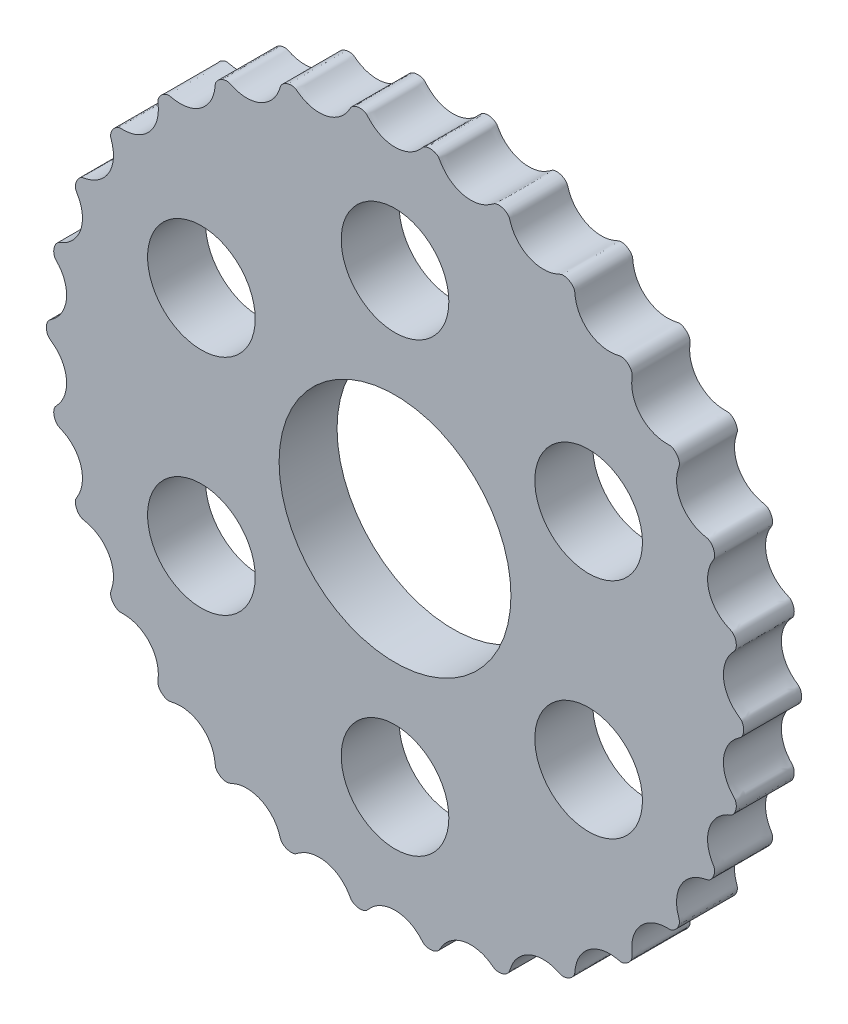
SolidWorks part; units mm, degrees
ref_plane "Front Plane" through (0, 0, 0) normal (0, 0, 1) x (1, 0, 0)
ref_plane "Top Plane" through (0, 0, 0) normal (0, 1, 0) x (1, 0, 0)
ref_plane "Right Plane" through (0, 0, 0) normal (1, 0, 0) x (0, 0, -1)
curve "Curve2"
sketch "Sketch4" plane through (0, 0, 0) normal (0, 0, 1) x (1, 0, 0)
  spline S0 degree 3 poles (2.0538, 40.2971) (0, 39.6094) (-2.0538, 40.2971) (-2.9937, 41.1501) (-3.2907, 41.4834) (-3.3948, 41.5967) (-3.4512, 41.6489) (-3.5086, 41.6916) (-3.588, 41.7387) (-3.6982, 41.7886) (-3.8407, 41.8344) (-4.0112, 41.8679) (-4.2015, 41.8823) (-4.4011, 41.8734) (-4.5981, 41.8406) (-4.7813, 41.787) (-4.9411, 41.7188) (-5.0709, 41.6443) (-5.1684, 41.5725) (-5.2363, 41.51) (-5.2836, 41.4563) (-5.3278, 41.3936) (-5.4061, 41.2611) (-5.6273, 40.8733) (-6.3694, 39.8436) (-8.2353, 38.7438) (-10.3871, 38.9896) (-11.4839, 39.6284) (-11.8437, 39.8927) (-11.9691, 39.9819) (-12.035, 40.0212) (-12.1001, 40.0511) (-12.1875, 40.0806) (-12.3058, 40.1065) (-12.4547, 40.1217) (-12.6284, 40.1191) (-12.8175, 40.0935) (-13.0109, 40.0433) (-13.1968, 39.9703) (-13.3648, 39.8798) (-13.5069, 39.7798) (-13.6184, 39.68) (-13.6989, 39.5895) (-13.7523, 39.5142) (-13.7873, 39.4518) (-13.8176, 39.3813) (-13.8666, 39.2354) (-14.0023, 38.8101) (-14.5141, 37.6486) (-16.1106, 36.1849) (-18.2665, 35.978) (-19.4721, 36.3748) (-19.879, 36.5586) (-20.0202, 36.6197) (-20.0929, 36.6444) (-20.1627, 36.6601) (-20.2544, 36.6708) (-20.3755, 36.6716) (-20.5243, 36.6555) (-20.6936, 36.6168) (-20.8734, 36.5525) (-21.052, 36.4632) (-21.2187, 36.3531) (-21.3642, 36.2296) (-21.4825, 36.1023) (-21.5708, 35.9815) (-21.6306, 35.8762) (-21.6672, 35.7915) (-21.6886, 35.7232) (-21.7035, 35.6479) (-21.7211, 35.495) (-21.7654, 35.0508) (-22.0246, 33.8083) (-23.2818, 32.0446) (-25.3476, 31.3939) (-26.6094, 31.5315) (-27.0456, 31.6265) (-27.1964, 31.657) (-27.2726, 31.6661) (-27.3442, 31.667) (-27.4361, 31.6583) (-27.5547, 31.6339) (-27.6969, 31.5872) (-27.8545, 31.5142) (-28.0169, 31.4139) (-28.1731, 31.2894) (-28.3132, 31.1471) (-28.4299, 30.996) (-28.5191, 30.8469) (-28.5804, 30.7104) (-28.6171, 30.595) (-28.6352, 30.5045) (-28.6419, 30.4332) (-28.6408, 30.3565) (-28.6263, 30.2033) (-28.5773, 29.7595) (-28.5724, 28.4903) (-29.4355, 26.5038) (-31.3209, 25.4378) (-32.5837, 25.31) (-33.0301, 25.3124) (-33.184, 25.3108) (-33.2604, 25.3038) (-33.3306, 25.2898) (-33.4187, 25.2622) (-33.5296, 25.2137) (-33.659, 25.1385) (-33.798, 25.0342) (-33.936, 24.9024) (-34.0629, 24.7482) (-34.1704, 24.5798) (-34.2531, 24.4078) (-34.3093, 24.2434) (-34.3409, 24.0971) (-34.3528, 23.9766) (-34.3517, 23.8843) (-34.3434, 23.8132) (-34.3264, 23.7384) (-34.2804, 23.5915) (-34.1402, 23.1677) (-33.8715, 21.9272) (-34.3027, 19.8047) (-35.9252, 18.3699) (-37.1339, 17.9824) (-37.571, 17.8919) (-37.7212, 17.8584) (-37.7945, 17.8356) (-37.8603, 17.8073) (-37.9407, 17.7621) (-38.0391, 17.6915) (-38.15, 17.591) (-38.2643, 17.4602) (-38.3719, 17.3025) (-38.464, 17.1253) (-38.5341, 16.9382) (-38.5793, 16.7528) (-38.6, 16.5803) (-38.6005, 16.4306) (-38.5871, 16.3103) (-38.5669, 16.2203) (-38.544, 16.1524) (-38.5118, 16.0828) (-38.4362, 15.9487) (-38.211, 15.5633) (-37.6902, 14.4057) (-37.6707, 12.24) (-38.9595, 10.4993) (-40.0612, 9.8689) (-40.47, 9.6894) (-40.6099, 9.6254) (-40.6769, 9.588) (-40.7353, 9.5466) (-40.8046, 9.4856) (-40.8861, 9.3961) (-40.9737, 9.2748) (-41.0583, 9.123) (-41.1308, 8.9465) (-41.184, 8.7539) (-41.2137, 8.5564) (-41.2193, 8.3656) (-41.2038, 8.1926) (-41.1731, 8.0461) (-41.135, 7.9312) (-41.0965, 7.8473) (-41.06, 7.7857) (-41.014, 7.7243) (-40.9122, 7.6089) (-40.6118, 7.2787) (-39.8617, 6.2547) (-39.3924, 4.1403) (-40.2911, 2.1697) (-41.2376, 1.324) (-41.6002, 1.0635) (-41.7237, 0.9718) (-41.7815, 0.9213) (-41.83, 0.8686) (-41.8851, 0.7946) (-41.9462, 0.6901) (-42.0067, 0.5532) (-42.0579, 0.3872) (-42.0921, 0.1994) (-42.1041, 0) (-42.0921, -0.1994) (-42.0579, -0.3872) (-42.0067, -0.5532) (-41.9462, -0.6901) (-41.8851, -0.7946) (-41.83, -0.8686) (-41.7815, -0.9213) (-41.7237, -0.9718) (-41.6002, -1.0635) (-41.2376, -1.324) (-40.2911, -2.1697) (-39.3924, -4.1403) (-39.8617, -6.2547) (-40.6118, -7.2787) (-40.9122, -7.6089) (-41.014, -7.7243) (-41.06, -7.7857) (-41.0965, -7.8473) (-41.135, -7.9312) (-41.1731, -8.0461) (-41.2038, -8.1926) (-41.2193, -8.3656) (-41.2137, -8.5564) (-41.184, -8.7539) (-41.1308, -8.9465) (-41.0583, -9.123) (-40.9737, -9.2748) (-40.8861, -9.3961) (-40.8046, -9.4856) (-40.7353, -9.5466) (-40.6769, -9.588) (-40.6099, -9.6254) (-40.47, -9.6894) (-40.0612, -9.8689) (-38.9595, -10.4993) (-37.6707, -12.24) (-37.6902, -14.4057) (-38.211, -15.5633) (-38.4362, -15.9487) (-38.5118, -16.0828) (-38.544, -16.1524) (-38.5669, -16.2203) (-38.5871, -16.3103) (-38.6005, -16.4306) (-38.6, -16.5803) (-38.5793, -16.7528) (-38.5341, -16.9382) (-38.464, -17.1253) (-38.3719, -17.3025) (-38.2643, -17.4602) (-38.15, -17.591) (-38.0391, -17.6915) (-37.9407, -17.7621) (-37.8603, -17.8073) (-37.7945, -17.8356) (-37.7212, -17.8584) (-37.571, -17.8919) (-37.1339, -17.9824) (-35.9252, -18.3699) (-34.3027, -19.8047) (-33.8715, -21.9272) (-34.1402, -23.1677) (-34.2804, -23.5915) (-34.3264, -23.7384) (-34.3434, -23.8132) (-34.3517, -23.8843) (-34.3528, -23.9766) (-34.3409, -24.0971) (-34.3093, -24.2434) (-34.2531, -24.4078) (-34.1704, -24.5798) (-34.0629, -24.7482) (-33.936, -24.9024) (-33.798, -25.0342) (-33.659, -25.1385) (-33.5296, -25.2137) (-33.4187, -25.2622) (-33.3306, -25.2898) (-33.2604, -25.3038) (-33.184, -25.3108) (-33.0301, -25.3124) (-32.5837, -25.31) (-31.3209, -25.4378) (-29.4355, -26.5038) (-28.5724, -28.4903) (-28.5773, -29.7595) (-28.6263, -30.2033) (-28.6408, -30.3565) (-28.6419, -30.4332) (-28.6352, -30.5045) (-28.6171, -30.595) (-28.5804, -30.7104) (-28.5191, -30.8469) (-28.4299, -30.996) (-28.3132, -31.1471) (-28.1731, -31.2894) (-28.0169, -31.4139) (-27.8545, -31.5142) (-27.6969, -31.5872) (-27.5547, -31.6339) (-27.4361, -31.6583) (-27.3442, -31.667) (-27.2726, -31.6661) (-27.1964, -31.657) (-27.0456, -31.6265) (-26.6094, -31.5315) (-25.3476, -31.3939) (-23.2818, -32.0446) (-22.0246, -33.8083) (-21.7654, -35.0508) (-21.7211, -35.495) (-21.7035, -35.6479) (-21.6886, -35.7232) (-21.6672, -35.7915) (-21.6306, -35.8762) (-21.5708, -35.9815) (-21.4825, -36.1023) (-21.3642, -36.2296) (-21.2187, -36.3531) (-21.052, -36.4632) (-20.8734, -36.5525) (-20.6936, -36.6168) (-20.5243, -36.6555) (-20.3755, -36.6716) (-20.2544, -36.6708) (-20.1627, -36.6601) (-20.0929, -36.6444) (-20.0202, -36.6197) (-19.879, -36.5586) (-19.4721, -36.3748) (-18.2665, -35.978) (-16.1106, -36.1849) (-14.5141, -37.6486) (-14.0023, -38.8101) (-13.8666, -39.2354) (-13.8176, -39.3813) (-13.7873, -39.4518) (-13.7523, -39.5142) (-13.6989, -39.5895) (-13.6184, -39.68) (-13.5069, -39.7798) (-13.3648, -39.8798) (-13.1968, -39.9703) (-13.0109, -40.0433) (-12.8175, -40.0935) (-12.6284, -40.1191) (-12.4547, -40.1217) (-12.3058, -40.1065) (-12.1875, -40.0806) (-12.1001, -40.0511) (-12.035, -40.0212) (-11.9691, -39.9819) (-11.8437, -39.8927) (-11.4839, -39.6284) (-10.3871, -38.9896) (-8.2353, -38.7438) (-6.3694, -39.8436) (-5.6273, -40.8733) (-5.4061, -41.2611) (-5.3278, -41.3936) (-5.2836, -41.4563) (-5.2363, -41.51) (-5.1684, -41.5725) (-5.0709, -41.6443) (-4.9411, -41.7188) (-4.7813, -41.787) (-4.5981, -41.8406) (-4.4011, -41.8734) (-4.2015, -41.8823) (-4.0112, -41.8679) (-3.8407, -41.8344) (-3.6982, -41.7886) (-3.588, -41.7387) (-3.5086, -41.6916) (-3.4512, -41.6489) (-3.3948, -41.5967) (-3.2907, -41.4834) (-2.9937, -41.1501) (-2.0538, -40.2971) (0, -39.6094) (2.0538, -40.2971) (2.9937, -41.1501) (3.2907, -41.4834) (3.3948, -41.5967) (3.4512, -41.6489) (3.5086, -41.6916) (3.588, -41.7387) (3.6982, -41.7886) (3.8407, -41.8344) (4.0112, -41.8679) (4.2015, -41.8823) (4.4011, -41.8734) (4.5981, -41.8406) (4.7813, -41.787) (4.9411, -41.7188) (5.0709, -41.6443) (5.1684, -41.5725) (5.2363, -41.51) (5.2836, -41.4563) (5.3278, -41.3936) (5.4061, -41.2611) (5.6273, -40.8733) (6.3694, -39.8436) (8.2353, -38.7438) (10.3871, -38.9896) (11.4839, -39.6284) (11.8437, -39.8927) (11.9691, -39.9819) (12.035, -40.0212) (12.1001, -40.0511) (12.1875, -40.0806) (12.3058, -40.1065) (12.4547, -40.1217) (12.6284, -40.1191) (12.8175, -40.0935) (13.0109, -40.0433) (13.1968, -39.9703) (13.3648, -39.8798) (13.5069, -39.7798) (13.6184, -39.68) (13.6989, -39.5895) (13.7523, -39.5142) (13.7873, -39.4518) (13.8176, -39.3813) (13.8666, -39.2354) (14.0023, -38.8101) (14.5141, -37.6486) (16.1106, -36.1849) (18.2665, -35.978) (19.4721, -36.3748) (19.879, -36.5586) (20.0202, -36.6197) (20.0929, -36.6444) (20.1627, -36.6601) (20.2544, -36.6708) (20.3755, -36.6716) (20.5243, -36.6555) (20.6936, -36.6168) (20.8734, -36.5525) (21.052, -36.4632) (21.2187, -36.3531) (21.3642, -36.2296) (21.4825, -36.1023) (21.5708, -35.9815) (21.6306, -35.8762) (21.6672, -35.7915) (21.6886, -35.7232) (21.7035, -35.6479) (21.7211, -35.495) (21.7654, -35.0508) (22.0246, -33.8083) (23.2818, -32.0446) (25.3476, -31.3939) (26.6094, -31.5315) (27.0456, -31.6265) (27.1964, -31.657) (27.2726, -31.6661) (27.3442, -31.667) (27.4361, -31.6583) (27.5547, -31.6339) (27.6969, -31.5872) (27.8545, -31.5142) (28.0169, -31.4139) (28.1731, -31.2894) (28.3132, -31.1471) (28.4299, -30.996) (28.5191, -30.8469) (28.5804, -30.7104) (28.6171, -30.595) (28.6352, -30.5045) (28.6419, -30.4332) (28.6408, -30.3565) (28.6263, -30.2033) (28.5773, -29.7595) (28.5724, -28.4903) (29.4355, -26.5038) (31.3209, -25.4378) (32.5837, -25.31) (33.0301, -25.3124) (33.184, -25.3108) (33.2604, -25.3038) (33.3306, -25.2898) (33.4187, -25.2622) (33.5296, -25.2137) (33.659, -25.1385) (33.798, -25.0342) (33.936, -24.9024) (34.0629, -24.7482) (34.1704, -24.5798) (34.2531, -24.4078) (34.3093, -24.2434) (34.3409, -24.0971) (34.3528, -23.9766) (34.3517, -23.8843) (34.3434, -23.8132) (34.3264, -23.7384) (34.2804, -23.5915) (34.1402, -23.1677) (33.8715, -21.9272) (34.3027, -19.8047) (35.9252, -18.3699) (37.1339, -17.9824) (37.571, -17.8919) (37.7212, -17.8584) (37.7945, -17.8356) (37.8603, -17.8073) (37.9407, -17.7621) (38.0391, -17.6915) (38.15, -17.591) (38.2643, -17.4602) (38.3719, -17.3025) (38.464, -17.1253) (38.5341, -16.9382) (38.5793, -16.7528) (38.6, -16.5803) (38.6005, -16.4306) (38.5871, -16.3103) (38.5669, -16.2203) (38.544, -16.1524) (38.5118, -16.0828) (38.4362, -15.9487) (38.211, -15.5633) (37.6902, -14.4057) (37.6707, -12.24) (38.9595, -10.4993) (40.0612, -9.8689) (40.47, -9.6894) (40.6099, -9.6254) (40.6769, -9.588) (40.7353, -9.5466) (40.8046, -9.4856) (40.8861, -9.3961) (40.9737, -9.2748) (41.0583, -9.123) (41.1308, -8.9465) (41.184, -8.7539) (41.2137, -8.5564) (41.2193, -8.3656) (41.2038, -8.1926) (41.1731, -8.0461) (41.135, -7.9312) (41.0965, -7.8473) (41.06, -7.7857) (41.014, -7.7243) (40.9122, -7.6089) (40.6118, -7.2787) (39.8617, -6.2547) (39.3924, -4.1403) (40.2911, -2.1697) (41.2376, -1.324) (41.6002, -1.0635) (41.7237, -0.9718) (41.7815, -0.9213) (41.83, -0.8686) (41.8851, -0.7946) (41.9462, -0.6901) (42.0067, -0.5532) (42.0579, -0.3872) (42.0921, -0.1994) (42.1041, 0) (42.0921, 0.1994) (42.0579, 0.3872) (42.0067, 0.5532) (41.9462, 0.6901) (41.8851, 0.7946) (41.83, 0.8686) (41.7815, 0.9213) (41.7237, 0.9718) (41.6002, 1.0635) (41.2376, 1.324) (40.2911, 2.1697) (39.3924, 4.1403) (39.8617, 6.2547) (40.6118, 7.2787) (40.9122, 7.6089) (41.014, 7.7243) (41.06, 7.7857) (41.0965, 7.8473) (41.135, 7.9312) (41.1731, 8.0461) (41.2038, 8.1926) (41.2193, 8.3656) (41.2137, 8.5564) (41.184, 8.7539) (41.1308, 8.9465) (41.0583, 9.123) (40.9737, 9.2748) (40.8861, 9.3961) (40.8046, 9.4856) (40.7353, 9.5466) (40.6769, 9.588) (40.6099, 9.6254) (40.47, 9.6894) (40.0612, 9.8689) (38.9595, 10.4993) (37.6707, 12.24) (37.6902, 14.4057) (38.211, 15.5633) (38.4362, 15.9487) (38.5118, 16.0828) (38.544, 16.1524) (38.5669, 16.2203) (38.5871, 16.3103) (38.6005, 16.4306) (38.6, 16.5803) (38.5793, 16.7528) (38.5341, 16.9382) (38.464, 17.1253) (38.3719, 17.3025) (38.2643, 17.4602) (38.15, 17.591) (38.0391, 17.6915) (37.9407, 17.7621) (37.8603, 17.8073) (37.7945, 17.8356) (37.7212, 17.8584) (37.571, 17.8919) (37.1339, 17.9824) (35.9252, 18.3699) (34.3027, 19.8047) (33.8715, 21.9272) (34.1402, 23.1677) (34.2804, 23.5915) (34.3264, 23.7384) (34.3434, 23.8132) (34.3517, 23.8843) (34.3528, 23.9766) (34.3409, 24.0971) (34.3093, 24.2434) (34.2531, 24.4078) (34.1704, 24.5798) (34.0629, 24.7482) (33.936, 24.9024) (33.798, 25.0342) (33.659, 25.1385) (33.5296, 25.2137) (33.4187, 25.2622) (33.3306, 25.2898) (33.2604, 25.3038) (33.184, 25.3108) (33.0301, 25.3124) (32.5837, 25.31) (31.3209, 25.4378) (29.4355, 26.5038) (28.5724, 28.4903) (28.5773, 29.7595) (28.6263, 30.2033) (28.6408, 30.3565) (28.6419, 30.4332) (28.6352, 30.5045) (28.6171, 30.595) (28.5804, 30.7104) (28.5191, 30.8469) (28.4299, 30.996) (28.3132, 31.1471) (28.1731, 31.2894) (28.0169, 31.4139) (27.8545, 31.5142) (27.6969, 31.5872) (27.5547, 31.6339) (27.4361, 31.6583) (27.3442, 31.667) (27.2726, 31.6661) (27.1964, 31.657) (27.0456, 31.6265) (26.6094, 31.5315) (25.3476, 31.3939) (23.2818, 32.0446) (22.0246, 33.8083) (21.7654, 35.0508) (21.7211, 35.495) (21.7035, 35.6479) (21.6886, 35.7232) (21.6672, 35.7915) (21.6306, 35.8762) (21.5708, 35.9815) (21.4825, 36.1023) (21.3642, 36.2296) (21.2187, 36.3531) (21.052, 36.4632) (20.8734, 36.5525) (20.6936, 36.6168) (20.5243, 36.6555) (20.3755, 36.6716) (20.2544, 36.6708) (20.1627, 36.6601) (20.0929, 36.6444) (20.0202, 36.6197) (19.879, 36.5586) (19.4721, 36.3748) (18.2665, 35.978) (16.1106, 36.1849) (14.5141, 37.6486) (14.0023, 38.8101) (13.8666, 39.2354) (13.8176, 39.3813) (13.7873, 39.4518) (13.7523, 39.5142) (13.6989, 39.5895) (13.6184, 39.68) (13.5069, 39.7798) (13.3648, 39.8798) (13.1968, 39.9703) (13.0109, 40.0433) (12.8175, 40.0935) (12.6284, 40.1191) (12.4547, 40.1217) (12.3058, 40.1065) (12.1875, 40.0806) (12.1001, 40.0511) (12.035, 40.0212) (11.9691, 39.9819) (11.8437, 39.8927) (11.4839, 39.6284) (10.3871, 38.9896) (8.2353, 38.7438) (6.3694, 39.8436) (5.6273, 40.8733) (5.4061, 41.2611) (5.3278, 41.3936) (5.2836, 41.4563) (5.2363, 41.51) (5.1684, 41.5725) (5.0709, 41.6443) (4.9411, 41.7188) (4.7813, 41.787) (4.5981, 41.8406) (4.4011, 41.8734) (4.2015, 41.8823) (4.0112, 41.8679) (3.8407, 41.8344) (3.6982, 41.7886) (3.588, 41.7387) (3.5086, 41.6916) (3.4512, 41.6489) (3.3948, 41.5967) (3.2907, 41.4834) (2.9937, 41.1501) (2.0538, 40.2971) (0, 39.6094) (-2.0538, 40.2971) knots -0.012752 -0.011755 -0.008603 0 0.008603 0.011755 0.012752 0.013108 0.013308 0.013526 0.013829 0.014237 0.014745 0.015336 0.015986 0.016667 0.017347 0.017997 0.018588 0.019096 0.019504 0.019807 0.020026 0.020225 0.020581 0.021578 0.024731 0.033333 0.041936 0.045089 0.046086 0.046442 0.046641 0.046859 0.047163 0.047571 0.048078 0.04867 0.04932 0.05 0.05068 0.05133 0.051922 0.052429 0.052837 0.053141 0.053359 0.053558 0.053914 0.054911 0.058064 0.066667 0.075269 0.078422 0.079419 0.079775 0.079974 0.080193 0.080496 0.080904 0.081412 0.082003 0.082653 0.083333 0.084014 0.084664 0.085255 0.085763 0.086171 0.086474 0.086692 0.086892 0.087248 0.088245 0.091397 0.1 0.108603 0.111755 0.112752 0.113108 0.113308 0.113526 0.113829 0.114237 0.114745 0.115336 0.115986 0.116667 0.117347 0.117997 0.118588 0.119096 0.119504 0.119807 0.120026 0.120225 0.120581 0.121578 0.124731 0.133333 0.141936 0.145089 0.146086 0.146442 0.146641 0.146859 0.147163 0.147571 0.148078 0.14867 0.14932 0.15 0.15068 0.15133 0.151922 0.15243 0.152837 0.153141 0.153359 0.153558 0.153914 0.154911 0.158064 0.166667 0.175269 0.178422 0.179419 0.179775 0.179974 0.180193 0.180496 0.180904 0.181412 0.182003 0.182653 0.183333 0.184014 0.184664 0.185255 0.185763 0.186171 0.186474 0.186692 0.186892 0.187248 0.188245 0.191397 0.2 0.208603 0.211755 0.212752 0.213108 0.213308 0.213526 0.213829 0.214237 0.214745 0.215336 0.215986 0.216667 0.217347 0.217997 0.218588 0.219096 0.219504 0.219807 0.220026 0.220225 0.220581 0.221578 0.224731 0.233333 0.241936 0.245089 0.246086 0.246442 0.246641 0.246859 0.247163 0.247571 0.248078 0.24867 0.24932 0.25 0.25068 0.25133 0.251922 0.252429 0.252837 0.253141 0.253359 0.253558 0.253914 0.254911 0.258064 0.266667 0.275269 0.278422 0.279419 0.279775 0.279974 0.280193 0.280496 0.280904 0.281412 0.282003 0.282653 0.283333 0.284014 0.284664 0.285255 0.285763 0.286171 0.286474 0.286692 0.286892 0.287248 0.288245 0.291397 0.3 0.308603 0.311755 0.312752 0.313108 0.313308 0.313526 0.313829 0.314237 0.314745 0.315336 0.315986 0.316667 0.317347 0.317997 0.318588 0.319096 0.319504 0.319807 0.320026 0.320225 0.320581 0.321578 0.324731 0.333333 0.341936 0.345089 0.346086 0.346442 0.346641 0.346859 0.347163 0.34757 0.348078 0.34867 0.34932 0.35 0.35068 0.35133 0.351922 0.352429 0.352837 0.353141 0.353359 0.353558 0.353914 0.354911 0.358064 0.366667 0.375269 0.378422 0.379419 0.379775 0.379974 0.380193 0.380496 0.380904 0.381412 0.382003 0.382653 0.383333 0.384014 0.384664 0.385255 0.385763 0.386171 0.386474 0.386692 0.386892 0.387248 0.388245 0.391397 0.4 0.408603 0.411755 0.412752 0.413108 0.413308 0.413526 0.413829 0.414237 0.414745 0.415336 0.415986 0.416667 0.417347 0.417997 0.418588 0.419096 0.419504 0.419807 0.420026 0.420225 0.420581 0.421578 0.424731 0.433333 0.441936 0.445089 0.446086 0.446442 0.446641 0.446859 0.447163 0.447571 0.448078 0.44867 0.44932 0.45 0.45068 0.45133 0.451922 0.452429 0.452837 0.453141 0.453359 0.453558 0.453914 0.454911 0.458064 0.466667 0.475269 0.478422 0.479419 0.479775 0.479974 0.480193 0.480496 0.480904 0.481412 0.482003 0.482653 0.483333 0.484014 0.484664 0.485255 0.485763 0.486171 0.486474 0.486692 0.486892 0.487248 0.488245 0.491397 0.5 0.508603 0.511755 0.512752 0.513108 0.513308 0.513526 0.513829 0.514237 0.514745 0.515336 0.515986 0.516667 0.517347 0.517997 0.518588 0.519096 0.519504 0.519807 0.520026 0.520225 0.520581 0.521578 0.524731 0.533333 0.541936 0.545089 0.546086 0.546442 0.546641 0.546859 0.547163 0.547571 0.548078 0.54867 0.54932 0.55 0.55068 0.55133 0.551922 0.552429 0.552837 0.553141 0.553359 0.553558 0.553914 0.554911 0.558064 0.566667 0.575269 0.578422 0.579419 0.579775 0.579974 0.580193 0.580496 0.580904 0.581412 0.582003 0.582653 0.583333 0.584014 0.584664 0.585255 0.585763 0.586171 0.586474 0.586692 0.586892 0.587248 0.588245 0.591397 0.6 0.608603 0.611755 0.612752 0.613108 0.613308 0.613526 0.613829 0.614237 0.614745 0.615336 0.615986 0.616667 0.617347 0.617997 0.618588 0.619096 0.619504 0.619807 0.620026 0.620225 0.620581 0.621578 0.624731 0.633333 0.641936 0.645089 0.646086 0.646442 0.646641 0.646859 0.647163 0.647571 0.648078 0.64867 0.64932 0.65 0.65068 0.65133 0.651922 0.65243 0.652837 0.653141 0.653359 0.653558 0.653914 0.654911 0.658064 0.666667 0.675269 0.678422 0.679419 0.679775 0.679974 0.680193 0.680496 0.680904 0.681412 0.682003 0.682653 0.683333 0.684014 0.684664 0.685255 0.685763 0.686171 0.686474 0.686692 0.686892 0.687248 0.688245 0.691397 0.7 0.708603 0.711755 0.712752 0.713108 0.713308 0.713526 0.713829 0.714237 0.714745 0.715336 0.715986 0.716667 0.717347 0.717997 0.718588 0.719096 0.719504 0.719807 0.720026 0.720225 0.720581 0.721578 0.724731 0.733333 0.741936 0.745089 0.746086 0.746442 0.746641 0.746859 0.747163 0.747571 0.748078 0.74867 0.74932 0.75 0.75068 0.75133 0.751922 0.752429 0.752837 0.753141 0.753359 0.753558 0.753914 0.754911 0.758064 0.766667 0.775269 0.778422 0.779419 0.779775 0.779974 0.780193 0.780496 0.780904 0.781412 0.782003 0.782653 0.783333 0.784014 0.784664 0.785255 0.785763 0.786171 0.786474 0.786692 0.786892 0.787248 0.788245 0.791397 0.8 0.808603 0.811755 0.812752 0.813108 0.813308 0.813526 0.813829 0.814237 0.814745 0.815336 0.815986 0.816667 0.817347 0.817997 0.818588 0.819096 0.819504 0.819807 0.820026 0.820225 0.820581 0.821578 0.824731 0.833333 0.841936 0.845089 0.846086 0.846442 0.846641 0.846859 0.847163 0.84757 0.848078 0.84867 0.84932 0.85 0.85068 0.85133 0.851922 0.852429 0.852837 0.853141 0.853359 0.853558 0.853914 0.854911 0.858064 0.866667 0.875269 0.878422 0.879419 0.879775 0.879974 0.880193 0.880496 0.880904 0.881412 0.882003 0.882653 0.883333 0.884014 0.884664 0.885255 0.885763 0.886171 0.886474 0.886692 0.886892 0.887248 0.888245 0.891397 0.9 0.908603 0.911755 0.912752 0.913108 0.913308 0.913526 0.913829 0.914237 0.914745 0.915336 0.915986 0.916667 0.917347 0.917997 0.918588 0.919096 0.919504 0.919807 0.920026 0.920225 0.920581 0.921578 0.924731 0.933333 0.941936 0.945089 0.946086 0.946442 0.946641 0.946859 0.947163 0.947571 0.948078 0.94867 0.94932 0.95 0.95068 0.95133 0.951922 0.952429 0.952837 0.953141 0.953359 0.953558 0.953914 0.954911 0.958064 0.966667 0.975269 0.978422 0.979419 0.979775 0.979974 0.980193 0.980496 0.980904 0.981412 0.982003 0.982653 0.983333 0.984014 0.984664 0.985255 0.985763 0.986171 0.986474 0.986692 0.986892 0.987248 0.988245 0.991397 1 1.008603 1.011755 1.012752 only from (0, 39.9) to (0, 39.9) construction
  spline S1 degree 3 poles (2.0538, 40.2971) (0, 39.6094) (-2.0538, 40.2971) (-2.9937, 41.1501) (-3.2907, 41.4834) (-3.3948, 41.5967) (-3.4512, 41.6489) (-3.5086, 41.6916) (-3.588, 41.7387) (-3.6982, 41.7886) (-3.8407, 41.8344) (-4.0112, 41.8679) (-4.2015, 41.8823) (-4.4011, 41.8734) (-4.5981, 41.8406) (-4.7813, 41.787) (-4.9411, 41.7188) (-5.0709, 41.6443) (-5.1684, 41.5725) (-5.2363, 41.51) (-5.2836, 41.4563) (-5.3278, 41.3936) (-5.4061, 41.2611) (-5.6273, 40.8733) (-6.3694, 39.8436) (-8.2353, 38.7438) (-10.3871, 38.9896) (-11.4839, 39.6284) (-11.8437, 39.8927) (-11.9691, 39.9819) (-12.035, 40.0212) (-12.1001, 40.0511) (-12.1875, 40.0806) (-12.3058, 40.1065) (-12.4547, 40.1217) (-12.6284, 40.1191) (-12.8175, 40.0935) (-13.0109, 40.0433) (-13.1968, 39.9703) (-13.3648, 39.8798) (-13.5069, 39.7798) (-13.6184, 39.68) (-13.6989, 39.5895) (-13.7523, 39.5142) (-13.7873, 39.4518) (-13.8176, 39.3813) (-13.8666, 39.2354) (-14.0023, 38.8101) (-14.5141, 37.6486) (-16.1106, 36.1849) (-18.2665, 35.978) (-19.4721, 36.3748) (-19.879, 36.5586) (-20.0202, 36.6197) (-20.0929, 36.6444) (-20.1627, 36.6601) (-20.2544, 36.6708) (-20.3755, 36.6716) (-20.5243, 36.6555) (-20.6936, 36.6168) (-20.8734, 36.5525) (-21.052, 36.4632) (-21.2187, 36.3531) (-21.3642, 36.2296) (-21.4825, 36.1023) (-21.5708, 35.9815) (-21.6306, 35.8762) (-21.6672, 35.7915) (-21.6886, 35.7232) (-21.7035, 35.6479) (-21.7211, 35.495) (-21.7654, 35.0508) (-22.0246, 33.8083) (-23.2818, 32.0446) (-25.3476, 31.3939) (-26.6094, 31.5315) (-27.0456, 31.6265) (-27.1964, 31.657) (-27.2726, 31.6661) (-27.3442, 31.667) (-27.4361, 31.6583) (-27.5547, 31.6339) (-27.6969, 31.5872) (-27.8545, 31.5142) (-28.0169, 31.4139) (-28.1731, 31.2894) (-28.3132, 31.1471) (-28.4299, 30.996) (-28.5191, 30.8469) (-28.5804, 30.7104) (-28.6171, 30.595) (-28.6352, 30.5045) (-28.6419, 30.4332) (-28.6408, 30.3565) (-28.6263, 30.2033) (-28.5773, 29.7595) (-28.5724, 28.4903) (-29.4355, 26.5038) (-31.3209, 25.4378) (-32.5837, 25.31) (-33.0301, 25.3124) (-33.184, 25.3108) (-33.2604, 25.3038) (-33.3306, 25.2898) (-33.4187, 25.2622) (-33.5296, 25.2137) (-33.659, 25.1385) (-33.798, 25.0342) (-33.936, 24.9024) (-34.0629, 24.7482) (-34.1704, 24.5798) (-34.2531, 24.4078) (-34.3093, 24.2434) (-34.3409, 24.0971) (-34.3528, 23.9766) (-34.3517, 23.8843) (-34.3434, 23.8132) (-34.3264, 23.7384) (-34.2804, 23.5915) (-34.1402, 23.1677) (-33.8715, 21.9272) (-34.3027, 19.8047) (-35.9252, 18.3699) (-37.1339, 17.9824) (-37.571, 17.8919) (-37.7212, 17.8584) (-37.7945, 17.8356) (-37.8603, 17.8073) (-37.9407, 17.7621) (-38.0391, 17.6915) (-38.15, 17.591) (-38.2643, 17.4602) (-38.3719, 17.3025) (-38.464, 17.1253) (-38.5341, 16.9382) (-38.5793, 16.7528) (-38.6, 16.5803) (-38.6005, 16.4306) (-38.5871, 16.3103) (-38.5669, 16.2203) (-38.544, 16.1524) (-38.5118, 16.0828) (-38.4362, 15.9487) (-38.211, 15.5633) (-37.6902, 14.4057) (-37.6707, 12.24) (-38.9595, 10.4993) (-40.0612, 9.8689) (-40.47, 9.6894) (-40.6099, 9.6254) (-40.6769, 9.588) (-40.7353, 9.5466) (-40.8046, 9.4856) (-40.8861, 9.3961) (-40.9737, 9.2748) (-41.0583, 9.123) (-41.1308, 8.9465) (-41.184, 8.7539) (-41.2137, 8.5564) (-41.2193, 8.3656) (-41.2038, 8.1926) (-41.1731, 8.0461) (-41.135, 7.9312) (-41.0965, 7.8473) (-41.06, 7.7857) (-41.014, 7.7243) (-40.9122, 7.6089) (-40.6118, 7.2787) (-39.8617, 6.2547) (-39.3924, 4.1403) (-40.2911, 2.1697) (-41.2376, 1.324) (-41.6002, 1.0635) (-41.7237, 0.9718) (-41.7815, 0.9213) (-41.83, 0.8686) (-41.8851, 0.7946) (-41.9462, 0.6901) (-42.0067, 0.5532) (-42.0579, 0.3872) (-42.0921, 0.1994) (-42.1041, 0) (-42.0921, -0.1994) (-42.0579, -0.3872) (-42.0067, -0.5532) (-41.9462, -0.6901) (-41.8851, -0.7946) (-41.83, -0.8686) (-41.7815, -0.9213) (-41.7237, -0.9718) (-41.6002, -1.0635) (-41.2376, -1.324) (-40.2911, -2.1697) (-39.3924, -4.1403) (-39.8617, -6.2547) (-40.6118, -7.2787) (-40.9122, -7.6089) (-41.014, -7.7243) (-41.06, -7.7857) (-41.0965, -7.8473) (-41.135, -7.9312) (-41.1731, -8.0461) (-41.2038, -8.1926) (-41.2193, -8.3656) (-41.2137, -8.5564) (-41.184, -8.7539) (-41.1308, -8.9465) (-41.0583, -9.123) (-40.9737, -9.2748) (-40.8861, -9.3961) (-40.8046, -9.4856) (-40.7353, -9.5466) (-40.6769, -9.588) (-40.6099, -9.6254) (-40.47, -9.6894) (-40.0612, -9.8689) (-38.9595, -10.4993) (-37.6707, -12.24) (-37.6902, -14.4057) (-38.211, -15.5633) (-38.4362, -15.9487) (-38.5118, -16.0828) (-38.544, -16.1524) (-38.5669, -16.2203) (-38.5871, -16.3103) (-38.6005, -16.4306) (-38.6, -16.5803) (-38.5793, -16.7528) (-38.5341, -16.9382) (-38.464, -17.1253) (-38.3719, -17.3025) (-38.2643, -17.4602) (-38.15, -17.591) (-38.0391, -17.6915) (-37.9407, -17.7621) (-37.8603, -17.8073) (-37.7945, -17.8356) (-37.7212, -17.8584) (-37.571, -17.8919) (-37.1339, -17.9824) (-35.9252, -18.3699) (-34.3027, -19.8047) (-33.8715, -21.9272) (-34.1402, -23.1677) (-34.2804, -23.5915) (-34.3264, -23.7384) (-34.3434, -23.8132) (-34.3517, -23.8843) (-34.3528, -23.9766) (-34.3409, -24.0971) (-34.3093, -24.2434) (-34.2531, -24.4078) (-34.1704, -24.5798) (-34.0629, -24.7482) (-33.936, -24.9024) (-33.798, -25.0342) (-33.659, -25.1385) (-33.5296, -25.2137) (-33.4187, -25.2622) (-33.3306, -25.2898) (-33.2604, -25.3038) (-33.184, -25.3108) (-33.0301, -25.3124) (-32.5837, -25.31) (-31.3209, -25.4378) (-29.4355, -26.5038) (-28.5724, -28.4903) (-28.5773, -29.7595) (-28.6263, -30.2033) (-28.6408, -30.3565) (-28.6419, -30.4332) (-28.6352, -30.5045) (-28.6171, -30.595) (-28.5804, -30.7104) (-28.5191, -30.8469) (-28.4299, -30.996) (-28.3132, -31.1471) (-28.1731, -31.2894) (-28.0169, -31.4139) (-27.8545, -31.5142) (-27.6969, -31.5872) (-27.5547, -31.6339) (-27.4361, -31.6583) (-27.3442, -31.667) (-27.2726, -31.6661) (-27.1964, -31.657) (-27.0456, -31.6265) (-26.6094, -31.5315) (-25.3476, -31.3939) (-23.2818, -32.0446) (-22.0246, -33.8083) (-21.7654, -35.0508) (-21.7211, -35.495) (-21.7035, -35.6479) (-21.6886, -35.7232) (-21.6672, -35.7915) (-21.6306, -35.8762) (-21.5708, -35.9815) (-21.4825, -36.1023) (-21.3642, -36.2296) (-21.2187, -36.3531) (-21.052, -36.4632) (-20.8734, -36.5525) (-20.6936, -36.6168) (-20.5243, -36.6555) (-20.3755, -36.6716) (-20.2544, -36.6708) (-20.1627, -36.6601) (-20.0929, -36.6444) (-20.0202, -36.6197) (-19.879, -36.5586) (-19.4721, -36.3748) (-18.2665, -35.978) (-16.1106, -36.1849) (-14.5141, -37.6486) (-14.0023, -38.8101) (-13.8666, -39.2354) (-13.8176, -39.3813) (-13.7873, -39.4518) (-13.7523, -39.5142) (-13.6989, -39.5895) (-13.6184, -39.68) (-13.5069, -39.7798) (-13.3648, -39.8798) (-13.1968, -39.9703) (-13.0109, -40.0433) (-12.8175, -40.0935) (-12.6284, -40.1191) (-12.4547, -40.1217) (-12.3058, -40.1065) (-12.1875, -40.0806) (-12.1001, -40.0511) (-12.035, -40.0212) (-11.9691, -39.9819) (-11.8437, -39.8927) (-11.4839, -39.6284) (-10.3871, -38.9896) (-8.2353, -38.7438) (-6.3694, -39.8436) (-5.6273, -40.8733) (-5.4061, -41.2611) (-5.3278, -41.3936) (-5.2836, -41.4563) (-5.2363, -41.51) (-5.1684, -41.5725) (-5.0709, -41.6443) (-4.9411, -41.7188) (-4.7813, -41.787) (-4.5981, -41.8406) (-4.4011, -41.8734) (-4.2015, -41.8823) (-4.0112, -41.8679) (-3.8407, -41.8344) (-3.6982, -41.7886) (-3.588, -41.7387) (-3.5086, -41.6916) (-3.4512, -41.6489) (-3.3948, -41.5967) (-3.2907, -41.4834) (-2.9937, -41.1501) (-2.0538, -40.2971) (0, -39.6094) (2.0538, -40.2971) (2.9937, -41.1501) (3.2907, -41.4834) (3.3948, -41.5967) (3.4512, -41.6489) (3.5086, -41.6916) (3.588, -41.7387) (3.6982, -41.7886) (3.8407, -41.8344) (4.0112, -41.8679) (4.2015, -41.8823) (4.4011, -41.8734) (4.5981, -41.8406) (4.7813, -41.787) (4.9411, -41.7188) (5.0709, -41.6443) (5.1684, -41.5725) (5.2363, -41.51) (5.2836, -41.4563) (5.3278, -41.3936) (5.4061, -41.2611) (5.6273, -40.8733) (6.3694, -39.8436) (8.2353, -38.7438) (10.3871, -38.9896) (11.4839, -39.6284) (11.8437, -39.8927) (11.9691, -39.9819) (12.035, -40.0212) (12.1001, -40.0511) (12.1875, -40.0806) (12.3058, -40.1065) (12.4547, -40.1217) (12.6284, -40.1191) (12.8175, -40.0935) (13.0109, -40.0433) (13.1968, -39.9703) (13.3648, -39.8798) (13.5069, -39.7798) (13.6184, -39.68) (13.6989, -39.5895) (13.7523, -39.5142) (13.7873, -39.4518) (13.8176, -39.3813) (13.8666, -39.2354) (14.0023, -38.8101) (14.5141, -37.6486) (16.1106, -36.1849) (18.2665, -35.978) (19.4721, -36.3748) (19.879, -36.5586) (20.0202, -36.6197) (20.0929, -36.6444) (20.1627, -36.6601) (20.2544, -36.6708) (20.3755, -36.6716) (20.5243, -36.6555) (20.6936, -36.6168) (20.8734, -36.5525) (21.052, -36.4632) (21.2187, -36.3531) (21.3642, -36.2296) (21.4825, -36.1023) (21.5708, -35.9815) (21.6306, -35.8762) (21.6672, -35.7915) (21.6886, -35.7232) (21.7035, -35.6479) (21.7211, -35.495) (21.7654, -35.0508) (22.0246, -33.8083) (23.2818, -32.0446) (25.3476, -31.3939) (26.6094, -31.5315) (27.0456, -31.6265) (27.1964, -31.657) (27.2726, -31.6661) (27.3442, -31.667) (27.4361, -31.6583) (27.5547, -31.6339) (27.6969, -31.5872) (27.8545, -31.5142) (28.0169, -31.4139) (28.1731, -31.2894) (28.3132, -31.1471) (28.4299, -30.996) (28.5191, -30.8469) (28.5804, -30.7104) (28.6171, -30.595) (28.6352, -30.5045) (28.6419, -30.4332) (28.6408, -30.3565) (28.6263, -30.2033) (28.5773, -29.7595) (28.5724, -28.4903) (29.4355, -26.5038) (31.3209, -25.4378) (32.5837, -25.31) (33.0301, -25.3124) (33.184, -25.3108) (33.2604, -25.3038) (33.3306, -25.2898) (33.4187, -25.2622) (33.5296, -25.2137) (33.659, -25.1385) (33.798, -25.0342) (33.936, -24.9024) (34.0629, -24.7482) (34.1704, -24.5798) (34.2531, -24.4078) (34.3093, -24.2434) (34.3409, -24.0971) (34.3528, -23.9766) (34.3517, -23.8843) (34.3434, -23.8132) (34.3264, -23.7384) (34.2804, -23.5915) (34.1402, -23.1677) (33.8715, -21.9272) (34.3027, -19.8047) (35.9252, -18.3699) (37.1339, -17.9824) (37.571, -17.8919) (37.7212, -17.8584) (37.7945, -17.8356) (37.8603, -17.8073) (37.9407, -17.7621) (38.0391, -17.6915) (38.15, -17.591) (38.2643, -17.4602) (38.3719, -17.3025) (38.464, -17.1253) (38.5341, -16.9382) (38.5793, -16.7528) (38.6, -16.5803) (38.6005, -16.4306) (38.5871, -16.3103) (38.5669, -16.2203) (38.544, -16.1524) (38.5118, -16.0828) (38.4362, -15.9487) (38.211, -15.5633) (37.6902, -14.4057) (37.6707, -12.24) (38.9595, -10.4993) (40.0612, -9.8689) (40.47, -9.6894) (40.6099, -9.6254) (40.6769, -9.588) (40.7353, -9.5466) (40.8046, -9.4856) (40.8861, -9.3961) (40.9737, -9.2748) (41.0583, -9.123) (41.1308, -8.9465) (41.184, -8.7539) (41.2137, -8.5564) (41.2193, -8.3656) (41.2038, -8.1926) (41.1731, -8.0461) (41.135, -7.9312) (41.0965, -7.8473) (41.06, -7.7857) (41.014, -7.7243) (40.9122, -7.6089) (40.6118, -7.2787) (39.8617, -6.2547) (39.3924, -4.1403) (40.2911, -2.1697) (41.2376, -1.324) (41.6002, -1.0635) (41.7237, -0.9718) (41.7815, -0.9213) (41.83, -0.8686) (41.8851, -0.7946) (41.9462, -0.6901) (42.0067, -0.5532) (42.0579, -0.3872) (42.0921, -0.1994) (42.1041, 0) (42.0921, 0.1994) (42.0579, 0.3872) (42.0067, 0.5532) (41.9462, 0.6901) (41.8851, 0.7946) (41.83, 0.8686) (41.7815, 0.9213) (41.7237, 0.9718) (41.6002, 1.0635) (41.2376, 1.324) (40.2911, 2.1697) (39.3924, 4.1403) (39.8617, 6.2547) (40.6118, 7.2787) (40.9122, 7.6089) (41.014, 7.7243) (41.06, 7.7857) (41.0965, 7.8473) (41.135, 7.9312) (41.1731, 8.0461) (41.2038, 8.1926) (41.2193, 8.3656) (41.2137, 8.5564) (41.184, 8.7539) (41.1308, 8.9465) (41.0583, 9.123) (40.9737, 9.2748) (40.8861, 9.3961) (40.8046, 9.4856) (40.7353, 9.5466) (40.6769, 9.588) (40.6099, 9.6254) (40.47, 9.6894) (40.0612, 9.8689) (38.9595, 10.4993) (37.6707, 12.24) (37.6902, 14.4057) (38.211, 15.5633) (38.4362, 15.9487) (38.5118, 16.0828) (38.544, 16.1524) (38.5669, 16.2203) (38.5871, 16.3103) (38.6005, 16.4306) (38.6, 16.5803) (38.5793, 16.7528) (38.5341, 16.9382) (38.464, 17.1253) (38.3719, 17.3025) (38.2643, 17.4602) (38.15, 17.591) (38.0391, 17.6915) (37.9407, 17.7621) (37.8603, 17.8073) (37.7945, 17.8356) (37.7212, 17.8584) (37.571, 17.8919) (37.1339, 17.9824) (35.9252, 18.3699) (34.3027, 19.8047) (33.8715, 21.9272) (34.1402, 23.1677) (34.2804, 23.5915) (34.3264, 23.7384) (34.3434, 23.8132) (34.3517, 23.8843) (34.3528, 23.9766) (34.3409, 24.0971) (34.3093, 24.2434) (34.2531, 24.4078) (34.1704, 24.5798) (34.0629, 24.7482) (33.936, 24.9024) (33.798, 25.0342) (33.659, 25.1385) (33.5296, 25.2137) (33.4187, 25.2622) (33.3306, 25.2898) (33.2604, 25.3038) (33.184, 25.3108) (33.0301, 25.3124) (32.5837, 25.31) (31.3209, 25.4378) (29.4355, 26.5038) (28.5724, 28.4903) (28.5773, 29.7595) (28.6263, 30.2033) (28.6408, 30.3565) (28.6419, 30.4332) (28.6352, 30.5045) (28.6171, 30.595) (28.5804, 30.7104) (28.5191, 30.8469) (28.4299, 30.996) (28.3132, 31.1471) (28.1731, 31.2894) (28.0169, 31.4139) (27.8545, 31.5142) (27.6969, 31.5872) (27.5547, 31.6339) (27.4361, 31.6583) (27.3442, 31.667) (27.2726, 31.6661) (27.1964, 31.657) (27.0456, 31.6265) (26.6094, 31.5315) (25.3476, 31.3939) (23.2818, 32.0446) (22.0246, 33.8083) (21.7654, 35.0508) (21.7211, 35.495) (21.7035, 35.6479) (21.6886, 35.7232) (21.6672, 35.7915) (21.6306, 35.8762) (21.5708, 35.9815) (21.4825, 36.1023) (21.3642, 36.2296) (21.2187, 36.3531) (21.052, 36.4632) (20.8734, 36.5525) (20.6936, 36.6168) (20.5243, 36.6555) (20.3755, 36.6716) (20.2544, 36.6708) (20.1627, 36.6601) (20.0929, 36.6444) (20.0202, 36.6197) (19.879, 36.5586) (19.4721, 36.3748) (18.2665, 35.978) (16.1106, 36.1849) (14.5141, 37.6486) (14.0023, 38.8101) (13.8666, 39.2354) (13.8176, 39.3813) (13.7873, 39.4518) (13.7523, 39.5142) (13.6989, 39.5895) (13.6184, 39.68) (13.5069, 39.7798) (13.3648, 39.8798) (13.1968, 39.9703) (13.0109, 40.0433) (12.8175, 40.0935) (12.6284, 40.1191) (12.4547, 40.1217) (12.3058, 40.1065) (12.1875, 40.0806) (12.1001, 40.0511) (12.035, 40.0212) (11.9691, 39.9819) (11.8437, 39.8927) (11.4839, 39.6284) (10.3871, 38.9896) (8.2353, 38.7438) (6.3694, 39.8436) (5.6273, 40.8733) (5.4061, 41.2611) (5.3278, 41.3936) (5.2836, 41.4563) (5.2363, 41.51) (5.1684, 41.5725) (5.0709, 41.6443) (4.9411, 41.7188) (4.7813, 41.787) (4.5981, 41.8406) (4.4011, 41.8734) (4.2015, 41.8823) (4.0112, 41.8679) (3.8407, 41.8344) (3.6982, 41.7886) (3.588, 41.7387) (3.5086, 41.6916) (3.4512, 41.6489) (3.3948, 41.5967) (3.2907, 41.4834) (2.9937, 41.1501) (2.0538, 40.2971) (0, 39.6094) (-2.0538, 40.2971) knots -0.012752 -0.011755 -0.008603 0 0.008603 0.011755 0.012752 0.013108 0.013308 0.013526 0.013829 0.014237 0.014745 0.015336 0.015986 0.016667 0.017347 0.017997 0.018588 0.019096 0.019504 0.019807 0.020026 0.020225 0.020581 0.021578 0.024731 0.033333 0.041936 0.045089 0.046086 0.046442 0.046641 0.046859 0.047163 0.047571 0.048078 0.04867 0.04932 0.05 0.05068 0.05133 0.051922 0.052429 0.052837 0.053141 0.053359 0.053558 0.053914 0.054911 0.058064 0.066667 0.075269 0.078422 0.079419 0.079775 0.079974 0.080193 0.080496 0.080904 0.081412 0.082003 0.082653 0.083333 0.084014 0.084664 0.085255 0.085763 0.086171 0.086474 0.086692 0.086892 0.087248 0.088245 0.091397 0.1 0.108603 0.111755 0.112752 0.113108 0.113308 0.113526 0.113829 0.114237 0.114745 0.115336 0.115986 0.116667 0.117347 0.117997 0.118588 0.119096 0.119504 0.119807 0.120026 0.120225 0.120581 0.121578 0.124731 0.133333 0.141936 0.145089 0.146086 0.146442 0.146641 0.146859 0.147163 0.147571 0.148078 0.14867 0.14932 0.15 0.15068 0.15133 0.151922 0.15243 0.152837 0.153141 0.153359 0.153558 0.153914 0.154911 0.158064 0.166667 0.175269 0.178422 0.179419 0.179775 0.179974 0.180193 0.180496 0.180904 0.181412 0.182003 0.182653 0.183333 0.184014 0.184664 0.185255 0.185763 0.186171 0.186474 0.186692 0.186892 0.187248 0.188245 0.191397 0.2 0.208603 0.211755 0.212752 0.213108 0.213308 0.213526 0.213829 0.214237 0.214745 0.215336 0.215986 0.216667 0.217347 0.217997 0.218588 0.219096 0.219504 0.219807 0.220026 0.220225 0.220581 0.221578 0.224731 0.233333 0.241936 0.245089 0.246086 0.246442 0.246641 0.246859 0.247163 0.247571 0.248078 0.24867 0.24932 0.25 0.25068 0.25133 0.251922 0.252429 0.252837 0.253141 0.253359 0.253558 0.253914 0.254911 0.258064 0.266667 0.275269 0.278422 0.279419 0.279775 0.279974 0.280193 0.280496 0.280904 0.281412 0.282003 0.282653 0.283333 0.284014 0.284664 0.285255 0.285763 0.286171 0.286474 0.286692 0.286892 0.287248 0.288245 0.291397 0.3 0.308603 0.311755 0.312752 0.313108 0.313308 0.313526 0.313829 0.314237 0.314745 0.315336 0.315986 0.316667 0.317347 0.317997 0.318588 0.319096 0.319504 0.319807 0.320026 0.320225 0.320581 0.321578 0.324731 0.333333 0.341936 0.345089 0.346086 0.346442 0.346641 0.346859 0.347163 0.34757 0.348078 0.34867 0.34932 0.35 0.35068 0.35133 0.351922 0.352429 0.352837 0.353141 0.353359 0.353558 0.353914 0.354911 0.358064 0.366667 0.375269 0.378422 0.379419 0.379775 0.379974 0.380193 0.380496 0.380904 0.381412 0.382003 0.382653 0.383333 0.384014 0.384664 0.385255 0.385763 0.386171 0.386474 0.386692 0.386892 0.387248 0.388245 0.391397 0.4 0.408603 0.411755 0.412752 0.413108 0.413308 0.413526 0.413829 0.414237 0.414745 0.415336 0.415986 0.416667 0.417347 0.417997 0.418588 0.419096 0.419504 0.419807 0.420026 0.420225 0.420581 0.421578 0.424731 0.433333 0.441936 0.445089 0.446086 0.446442 0.446641 0.446859 0.447163 0.447571 0.448078 0.44867 0.44932 0.45 0.45068 0.45133 0.451922 0.452429 0.452837 0.453141 0.453359 0.453558 0.453914 0.454911 0.458064 0.466667 0.475269 0.478422 0.479419 0.479775 0.479974 0.480193 0.480496 0.480904 0.481412 0.482003 0.482653 0.483333 0.484014 0.484664 0.485255 0.485763 0.486171 0.486474 0.486692 0.486892 0.487248 0.488245 0.491397 0.5 0.508603 0.511755 0.512752 0.513108 0.513308 0.513526 0.513829 0.514237 0.514745 0.515336 0.515986 0.516667 0.517347 0.517997 0.518588 0.519096 0.519504 0.519807 0.520026 0.520225 0.520581 0.521578 0.524731 0.533333 0.541936 0.545089 0.546086 0.546442 0.546641 0.546859 0.547163 0.547571 0.548078 0.54867 0.54932 0.55 0.55068 0.55133 0.551922 0.552429 0.552837 0.553141 0.553359 0.553558 0.553914 0.554911 0.558064 0.566667 0.575269 0.578422 0.579419 0.579775 0.579974 0.580193 0.580496 0.580904 0.581412 0.582003 0.582653 0.583333 0.584014 0.584664 0.585255 0.585763 0.586171 0.586474 0.586692 0.586892 0.587248 0.588245 0.591397 0.6 0.608603 0.611755 0.612752 0.613108 0.613308 0.613526 0.613829 0.614237 0.614745 0.615336 0.615986 0.616667 0.617347 0.617997 0.618588 0.619096 0.619504 0.619807 0.620026 0.620225 0.620581 0.621578 0.624731 0.633333 0.641936 0.645089 0.646086 0.646442 0.646641 0.646859 0.647163 0.647571 0.648078 0.64867 0.64932 0.65 0.65068 0.65133 0.651922 0.65243 0.652837 0.653141 0.653359 0.653558 0.653914 0.654911 0.658064 0.666667 0.675269 0.678422 0.679419 0.679775 0.679974 0.680193 0.680496 0.680904 0.681412 0.682003 0.682653 0.683333 0.684014 0.684664 0.685255 0.685763 0.686171 0.686474 0.686692 0.686892 0.687248 0.688245 0.691397 0.7 0.708603 0.711755 0.712752 0.713108 0.713308 0.713526 0.713829 0.714237 0.714745 0.715336 0.715986 0.716667 0.717347 0.717997 0.718588 0.719096 0.719504 0.719807 0.720026 0.720225 0.720581 0.721578 0.724731 0.733333 0.741936 0.745089 0.746086 0.746442 0.746641 0.746859 0.747163 0.747571 0.748078 0.74867 0.74932 0.75 0.75068 0.75133 0.751922 0.752429 0.752837 0.753141 0.753359 0.753558 0.753914 0.754911 0.758064 0.766667 0.775269 0.778422 0.779419 0.779775 0.779974 0.780193 0.780496 0.780904 0.781412 0.782003 0.782653 0.783333 0.784014 0.784664 0.785255 0.785763 0.786171 0.786474 0.786692 0.786892 0.787248 0.788245 0.791397 0.8 0.808603 0.811755 0.812752 0.813108 0.813308 0.813526 0.813829 0.814237 0.814745 0.815336 0.815986 0.816667 0.817347 0.817997 0.818588 0.819096 0.819504 0.819807 0.820026 0.820225 0.820581 0.821578 0.824731 0.833333 0.841936 0.845089 0.846086 0.846442 0.846641 0.846859 0.847163 0.84757 0.848078 0.84867 0.84932 0.85 0.85068 0.85133 0.851922 0.852429 0.852837 0.853141 0.853359 0.853558 0.853914 0.854911 0.858064 0.866667 0.875269 0.878422 0.879419 0.879775 0.879974 0.880193 0.880496 0.880904 0.881412 0.882003 0.882653 0.883333 0.884014 0.884664 0.885255 0.885763 0.886171 0.886474 0.886692 0.886892 0.887248 0.888245 0.891397 0.9 0.908603 0.911755 0.912752 0.913108 0.913308 0.913526 0.913829 0.914237 0.914745 0.915336 0.915986 0.916667 0.917347 0.917997 0.918588 0.919096 0.919504 0.919807 0.920026 0.920225 0.920581 0.921578 0.924731 0.933333 0.941936 0.945089 0.946086 0.946442 0.946641 0.946859 0.947163 0.947571 0.948078 0.94867 0.94932 0.95 0.95068 0.95133 0.951922 0.952429 0.952837 0.953141 0.953359 0.953558 0.953914 0.954911 0.958064 0.966667 0.975269 0.978422 0.979419 0.979775 0.979974 0.980193 0.980496 0.980904 0.981412 0.982003 0.982653 0.983333 0.984014 0.984664 0.985255 0.985763 0.986171 0.986474 0.986692 0.986892 0.987248 0.988245 0.991397 1 1.008603 1.011755 1.012752 only from (0, 39.9) to (0, 39.9)
extrude "Boss-Extrude2" add sketch "Sketch4" along normal blind 7
sketch "Sketch5" plane through (0, 0, 7) normal (0, 0, 1) x (1, 0, 0)
  line L0 (0, -1000) -> (0, 49000) construction
  circle A0 centre (0, 0) radius 14
  circle A1 centre (0, 27) radius 6.5
  circle A2 centre (23.3827, 13.5) radius 6.5
  circle A3 centre (23.3827, -13.5) radius 6.5
  circle A4 centre (0, -27) radius 6.5
  circle A5 centre (-23.3827, -13.5) radius 6.5
  circle A6 centre (-23.3827, 13.5) radius 6.5
  point P19 (0, 0)
  dimension "D1" = 28
  dimension "D3" = 13
  dimension "D2" = 27
  dimension "D4" = 6
extrude "Cut-Extrude2" cut sketch "Sketch5" against normal blind 7
